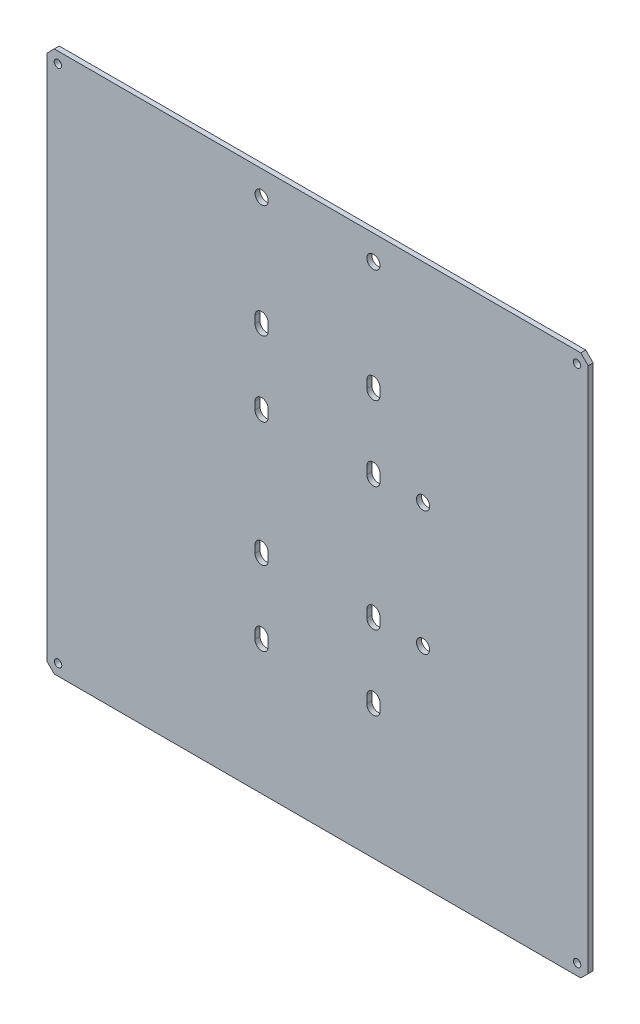
SolidWorks part; units mm, degrees
ref_plane "Front Plane" through (0, 0, 0) normal (0, 0, 1) x (1, 0, 0)
ref_plane "Top Plane" through (0, 0, 0) normal (0, 1, 0) x (1, 0, 0)
ref_plane "Right Plane" through (0, 0, 0) normal (1, 0, 0) x (0, 0, -1)
sketch "Sketch1" plane through (0, 0, 0) normal (0, 0, 1) x (1, 0, 0)
  line L0 (0, 109) -> (0, -109) construction
  line L1 (-109, -109) -> (109, -109)
  line L2 (-109, -109) -> (-109, 109)
  line L3 (-109, 109) -> (109, 109)
  line L4 (109, -109) -> (109, 109)
  line L5 (-109, -109) -> (109, 109) construction
  line L6 (-109, 109) -> (109, -109) construction
  line L7 (-22.5, 56.5) -> (-22.5, 53.5) construction
  line L8 (-22.5, 25) -> (22.5, 25) construction
  line L9 (-22.5, 25) -> (-22.5, 55) construction
  line L10 (-22.5, 55) -> (22.5, 55) construction
  line L11 (22.5, 25) -> (22.5, 55) construction
  line L12 (-22.5, 25) -> (22.5, 55) construction
  line L13 (-22.5, 55) -> (22.5, 25) construction
  line L14 (-22.5, -55) -> (22.5, -55) construction
  line L15 (-22.5, -55) -> (-22.5, -25) construction
  line L16 (-22.5, -25) -> (22.5, -25) construction
  line L17 (22.5, -55) -> (22.5, -25) construction
  line L18 (-22.5, -55) -> (22.5, -25) construction
  line L19 (-22.5, -25) -> (22.5, -55) construction
  line L20 (-19.85, 56.5) -> (-19.85, 53.5)
  line L21 (-25.15, 56.5) -> (-25.15, 53.5)
  line L22 (-22.5, 23.5) -> (-22.5, 26.5) construction
  line L23 (-25.15, 23.5) -> (-25.15, 26.5)
  line L24 (-19.85, 23.5) -> (-19.85, 26.5)
  line L25 (22.5, 56.5) -> (22.5, 53.5) construction
  line L26 (25.15, 56.5) -> (25.15, 53.5)
  line L27 (19.85, 56.5) -> (19.85, 53.5)
  line L28 (22.5, 23.5) -> (22.5, 26.5) construction
  line L29 (19.85, 23.5) -> (19.85, 26.5)
  line L30 (25.15, 23.5) -> (25.15, 26.5)
  line L31 (22.5, -23.5) -> (22.5, -26.5) construction
  line L32 (25.15, -23.5) -> (25.15, -26.5)
  line L33 (19.85, -23.5) -> (19.85, -26.5)
  line L34 (22.5, -56.5) -> (22.5, -53.5) construction
  line L35 (19.85, -56.5) -> (19.85, -53.5)
  line L36 (25.15, -56.5) -> (25.15, -53.5)
  line L37 (-22.5, -23.5) -> (-22.5, -26.5) construction
  line L38 (-19.85, -23.5) -> (-19.85, -26.5)
  line L39 (-25.15, -23.5) -> (-25.15, -26.5)
  line L40 (-22.5, -56.5) -> (-22.5, -53.5) construction
  line L41 (-25.15, -56.5) -> (-25.15, -53.5)
  line L42 (-19.85, -56.5) -> (-19.85, -53.5)
  line L43 (-8.5078, -55) -> (-8.5078, -109) construction
  line L44 (-11.0799, 55) -> (-11.0799, 109) construction
  line L45 (-22.5, 25) -> (42.5, 25) construction
  line L46 (-22.5, -25) -> (42.5, -25) construction
  line L47 (-109, 99) -> (109, 99) construction
  circle A0 centre (-104.5263, 104.5263) radius 1.5
  circle A1 centre (104.4737, 104.4737) radius 1.5
  circle A2 centre (104.5263, -104.5263) radius 1.5
  circle A3 centre (-104.4737, -104.4737) radius 1.5
  arc A4 (-19.85, 56.5) -> (-25.15, 56.5) centre (-22.5, 56.5) ccw
  arc A5 (-25.15, 53.5) -> (-19.85, 53.5) centre (-22.5, 53.5) ccw
  arc A6 (-25.15, 23.5) -> (-19.85, 23.5) centre (-22.5, 23.5) ccw
  arc A7 (-19.85, 26.5) -> (-25.15, 26.5) centre (-22.5, 26.5) ccw
  arc A8 (25.15, 56.5) -> (19.85, 56.5) centre (22.5, 56.5) ccw
  arc A9 (19.85, 53.5) -> (25.15, 53.5) centre (22.5, 53.5) ccw
  arc A10 (19.85, 23.5) -> (25.15, 23.5) centre (22.5, 23.5) ccw
  arc A11 (25.15, 26.5) -> (19.85, 26.5) centre (22.5, 26.5) ccw
  arc A12 (25.15, -23.5) -> (19.85, -23.5) centre (22.5, -23.5) ccw
  arc A13 (19.85, -26.5) -> (25.15, -26.5) centre (22.5, -26.5) ccw
  arc A14 (19.85, -56.5) -> (25.15, -56.5) centre (22.5, -56.5) ccw
  arc A15 (25.15, -53.5) -> (19.85, -53.5) centre (22.5, -53.5) ccw
  arc A16 (-19.85, -23.5) -> (-25.15, -23.5) centre (-22.5, -23.5) ccw
  arc A17 (-25.15, -26.5) -> (-19.85, -26.5) centre (-22.5, -26.5) ccw
  arc A18 (-25.15, -56.5) -> (-19.85, -56.5) centre (-22.5, -56.5) ccw
  arc A19 (-19.85, -53.5) -> (-25.15, -53.5) centre (-22.5, -53.5) ccw
  circle A20 centre (42.5, 25) radius 2.65
  circle A21 centre (42.5, -25) radius 2.65
  circle A22 centre (-22.5, 99) radius 2.65
  circle A23 centre (22.5, 99) radius 2.65
  point P0 (0, 0)
  point P16 (0, 40)
  point P21 (0, -40)
  point P28 (-22.5, 55)
  point P34 (-22.5, 25)
  point P41 (22.5, 55)
  point P48 (22.5, 25)
  point P55 (22.5, -25)
  point P63 (22.5, -55)
  point P69 (-22.5, -25)
  point P76 (-22.5, -55)
  dimension "D6" = 3
  dimension "D10" = 20
  dimension "D12" = 5.3
  dimension "D14" = 5.3
  dimension "D1" = 218
  dimension "D2" = 218
  dimension "D3" = 209
  dimension "D4" = 209
  dimension "D5" = 209
  dimension "D7" = 45
  dimension "D8" = 30
  dimension "D9" = 50
  dimension "D11" = 20
  dimension "D13" = 45
  dimension "D15" = 10
extrude "Boss-Extrude1" add sketch "Sketch1" along normal blind 2
chamfer "Chamfer1" distance 3 angle 45 4 edges at (109, 109, 1) (-109, 109, 1) (109, -109, 1) (-109, -109, 1)
